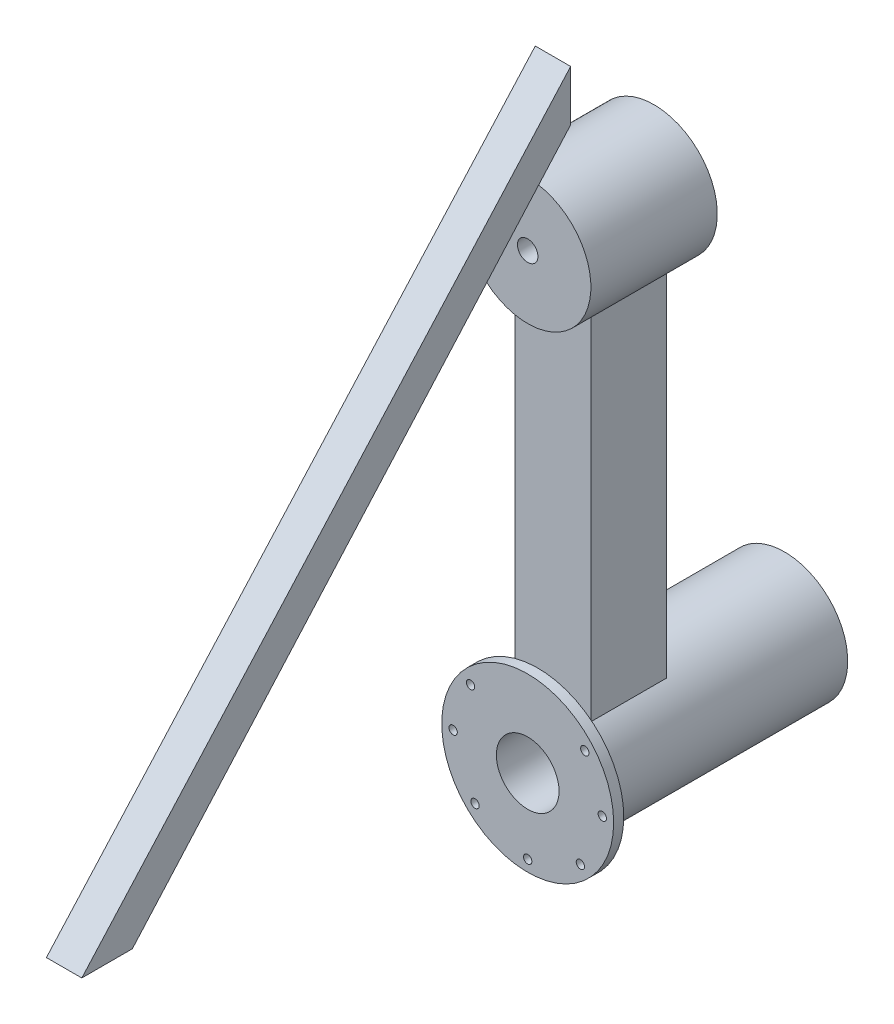
SolidWorks part; units mm, degrees
ref_plane "Alzado" through (0, 0, 0) normal (0, 0, 1) x (1, 0, 0)
ref_plane "Planta" through (0, 0, 0) normal (0, 1, 0) x (1, 0, 0)
ref_plane "Vista lateral" through (0, 0, 0) normal (1, 0, 0) x (0, 0, -1)
sketch "Croquis1" plane through (0, 0, 0) normal (0, 0, 1) x (1, 0, 0)
  circle A0 centre (0, 0) radius 25
  dimension "D1" = 50
extrude "Saliente-Extruir1" add sketch "Croquis1" along normal blind 270
sketch "Croquis2" plane through (0, 0, 0) normal (0, 1, 0) x (1, 0, 0)
  line L3 (-15.05, -11.6046) -> (14.95, -11.6046)
  line L4 (-15.05, -11.6046) -> (-15.05, -41.6046)
  line L5 (-15.05, -41.6046) -> (14.95, -41.6046)
  line L6 (14.95, -11.6046) -> (14.95, -41.6046)
  line L7 (-15.05, -11.6046) -> (14.95, -41.6046) construction
  line L8 (-15.05, -41.6046) -> (14.95, -11.6046) construction
  dimension "D1" = 30
  dimension "D3" = 30
extrude "Saliente-Extruir13" add sketch "Croquis2" along normal blind 150
ref_plane "Plano5" through (0, 0, 11.6046) normal (0, 0, -1) x (-1, 0, 0)
sketch "Croquis14" plane through (0, 0, 11.6046) normal (0, 0, -1) x (-1, 0, 0)
  line L1 (0, 0) -> (0, 179) construction
  circle A1 centre (0, 179) radius 25
  dimension "D3" = 50
  dimension "D2" = 179
extrude "Saliente-Extruir14" add sketch "Croquis14" along normal blind 10 and the other way blind 40
ref_plane "Plano6" through (0, 0, 1.6046) normal (0, 0, -1) x (-1, 0, 0)
sketch "Croquis15" plane through (0, 0, 0) normal (1, 0, 0) x (0, 0, -1)
  line L0 (-41.6046, 240.6046) -> (-235, 25)
  line L2 (-41.6046, 25) -> (-270, 25) construction
  line L4 (-41.6046, 150) -> (-41.6046, 20.0374) construction
  line L5 (-235, 25) -> (-215, 25)
  line L6 (-41.6046, 240.6046) -> (-41.6046, 220.6046)
  line L7 (-41.6046, 220.6046) -> (-215, 25)
  dimension "D3" = 20
  dimension "D4" = 20
extrude "Saliente-Extruir15" add sketch "Croquis15" along normal blind 7 and the other way blind 7 separate body
ref_plane "Plano9" through (0, 0, 0) normal (0, 0, -1) x (-1, 0, 0)
sketch "Croquis17" plane through (0, 0, 0) normal (0, 0, -1) x (-1, 0, 0)
  circle A0 centre (0, 0) radius 25
  dimension "D1" = 50
extrude "Saliente-Extruir16" add sketch "Croquis17" along normal blind 50
ref_plane "Plano10" through (0, 0, -50) normal (0, 0, -1) x (-1, 0, 0)
ref_plane "Plano11" through (0, 0, 1.6046) normal (0, 0, -1) x (-1, 0, 0)
sketch "Croquis19" plane through (0, 0, 1.6046) normal (0, 0, -1) x (-1, 0, 0)
  circle A1 centre (0, 179) radius 3.95
  dimension "D2" = 7.9
extrude "Saliente-Extruir17" [suppressed] add sketch "Croquis19" along normal blind 50
sketch "Croquis20" plane through (0, 0, -50) normal (0, 0, -1) x (-1, 0, 0)
  circle A0 centre (0, 0) radius 3.95
  dimension "D1" = 7.9
extrude "Saliente-Extruir18" add sketch "Croquis20" along normal blind 6
ref_plane "Plano12" through (0, 0, 270) normal (0, 0, 1) x (1, 0, 0)
sketch "Croquis21" plane through (0, 0, 270) normal (0, 0, 1) x (1, 0, 0)
  circle A0 centre (0, 0) radius 2.05
  dimension "D1" = 4.1
extrude "Cortar-Extruir2" cut sketch "Croquis21" against normal blind 10
ref_plane "Plano13" through (0, -25, 0) normal (0, -1, 0) x (-1, 0, 0)
sketch "Croquis22" plane through (0, -25, 0) normal (0, -1, 0) x (-1, 0, 0)
  line L6 (-10, 14.1977) -> (10, 14.1977)
  line L7 (-10, 14.1977) -> (-10, 34.1977)
  line L8 (-10, 34.1977) -> (10, 34.1977)
  line L9 (10, 14.1977) -> (10, 34.1977)
  dimension "D1" = 20
  dimension "D2" = 20
extrude "Cortar-Extruir3" cut sketch "Croquis22" against normal blind 20
sketch "Croquis23" plane through (0, 0, 0) normal (1, 0, 0) x (0, 0, -1)
  line L0 (-51.6046, 125) -> (-51.6046, -71.0891) construction
  line L1 (-51.6046, 175) -> (-51.6046, 125) construction
  line L2 (-270, 0) -> (-51.6046, 0) construction
  line L3 (-270, 27.5) -> (-270, -27.5) construction
  dimension "D1" = 218.3954
sketch "Croquis25" plane through (0, 0, -50) normal (0, 0, -1) x (-1, 0, 0)
  line L0 (0, 0) -> (0, 179) construction
  dimension "D1" = 179
sketch "Croquis27" plane through (0, 0, 11.6046) normal (0, 0, -1) x (-1, 0, 0)
  line L0 (-14.95, 150) -> (-14.95, 158.9626)
  line L1 (-14.95, 150) -> (15.05, 150)
  line L2 (15.05, 150) -> (15.05, 159.0376)
  arc A0 (-14.95, 158.9626) -> (15.05, 159.0376) centre (0, 179) ccw
extrude "Saliente-Extruir19" add sketch "Croquis27" against normal blind 30
sketch "Croquis28" plane through (0, 0, 270) normal (0, 0, 1) x (1, 0, 0)
  circle A0 centre (0, 0) radius 26.403
extrude "Cortar-Extruir4" cut sketch "Croquis28" against normal blind 218.4
sketch "Croquis29" plane through (0, 0, -50) normal (0, 0, -1) x (-1, 0, 0)
  circle A0 centre (0, 0) radius 34.2646
extrude "Cortar-Extruir5" cut sketch "Croquis29" along normal blind 218.4
sketch "Croquis30" plane through (0, 0, 51.6) normal (0, 0, 1) x (1, 0, 0)
  circle A0 centre (0, 0) radius 12.4
  dimension "D1" = 24.8
extrude "Cortar-Extruir6" cut sketch "Croquis30" against normal blind 30.1
sketch "Croquis31" plane through (0, 0, 1.6046) normal (0, 0, -1) x (-1, 0, 0)
  circle A0 centre (0, 179) radius 4.05
  dimension "D1" = 8.1
extrude "Cortar-Extruir7" cut sketch "Croquis31" against normal blind 60
sketch "Croquis32" plane through (0, 0, 51.6) normal (0, 0, 1) x (1, 0, 0)
  line L0 (0, 0) -> (-41.4248, 0) construction
  line L1 (0, 0) -> (-37.1286, 31.1546) construction
  line L2 (0, 0) -> (0, -44.2697) construction
  line L3 (0, 125) -> (0, -71.0891) construction
  line L4 (0, 0) -> (-37.4332, -37.4332) construction
  line L5 (0, 0) -> (-29.5, 0) construction
  circle A0 centre (0, 0) radius 25
  circle A1 centre (0, 0) radius 34
  circle A2 centre (0, 0) radius 29.5 construction
  circle A3 centre (-22.5983, 18.9622) radius 1.65
  circle A4 centre (-29.5, 0) radius 1.65
  circle A5 centre (-20.8394, -20.8394) radius 1.65
  circle A6 centre (0, -29.5) radius 1.65
  circle A7 centre (20.8394, -20.8394) radius 1.65
  circle A8 centre (29.5, 0) radius 1.65
  circle A9 centre (22.5983, 18.9622) radius 1.65
  dimension "D1" = 9
  dimension "D2" = 4.5
  dimension "D5" = 3.3
  dimension "D6" = 3.3
  dimension "D7" = 3.3
  dimension "D8" = 3.3
  dimension "D9" = 68
  dimension "D3" = 40
  dimension "D4" = 45
extrude "Saliente-Extruir20" add sketch "Croquis32" against normal blind 4
